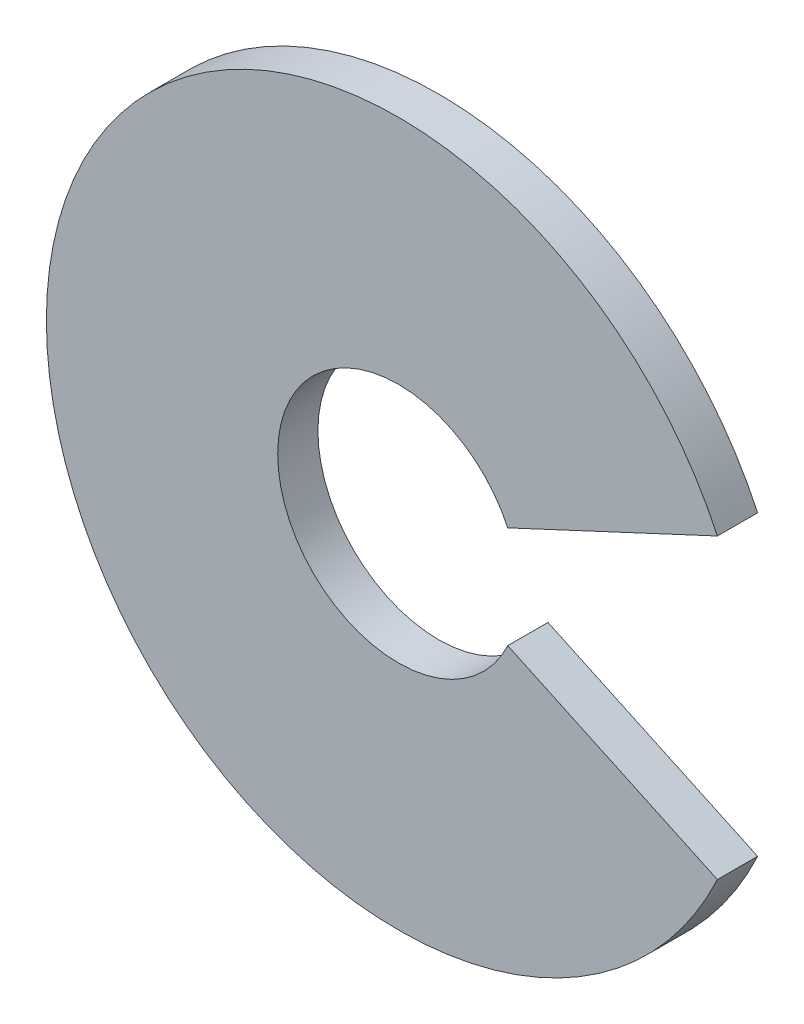
SolidWorks part; units mm, degrees
ref_plane "前视基准面" through (0, 0, 0) normal (0, 0, 1) x (1, 0, 0)
ref_plane "上视基准面" through (0, 0, 0) normal (0, 1, 0) x (1, 0, 0)
ref_plane "右视基准面" through (0, 0, 0) normal (1, 0, 0) x (0, 0, -1)
other "Configuration Table"
sketch "草图1" plane through (0, 0, 0) normal (0, 0, 1) x (1, 0, 0)
  line L0 (3.1721, -1.4792) -> (1.0876, -0.5071)
  line L1 (1.0876, 0.5071) -> (3.1721, 1.4792)
  arc A0 (3.1721, 1.4792) -> (3.1721, -1.4792) centre (0, 0) ccw
  arc A1 (1.0876, -0.5071) -> (1.0876, 0.5071) centre (0, 0) cw
extrude "凸台-拉伸1" add sketch "草图1" along normal mid plane 0.4
